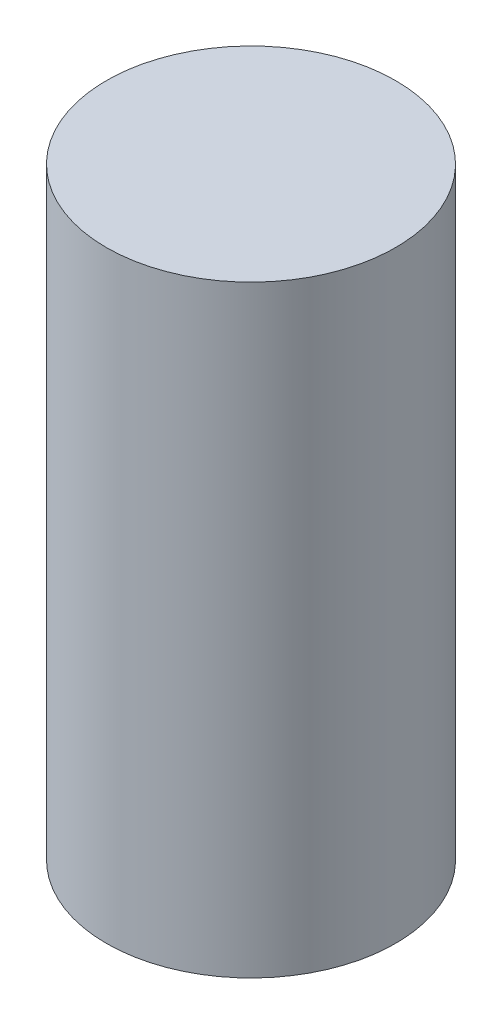
SolidWorks part; units mm, degrees
ref_plane "Front Plane" through (0, 0, 0) normal (0, 0, 1) x (1, 0, 0)
ref_plane "Top Plane" through (0, 0, 0) normal (0, 1, 0) x (1, 0, 0)
ref_plane "Right Plane" through (0, 0, 0) normal (1, 0, 0) x (0, 0, -1)
sketch "Sketch1" plane through (0, 0, 0) normal (0, 1, 0) x (1, 0, 0)
  circle A0 centre (0, 0) radius 4.7625
  dimension "D1" = 9.525
extrude "Boss-Extrude1" add sketch "Sketch1" along normal blind 19.8438
